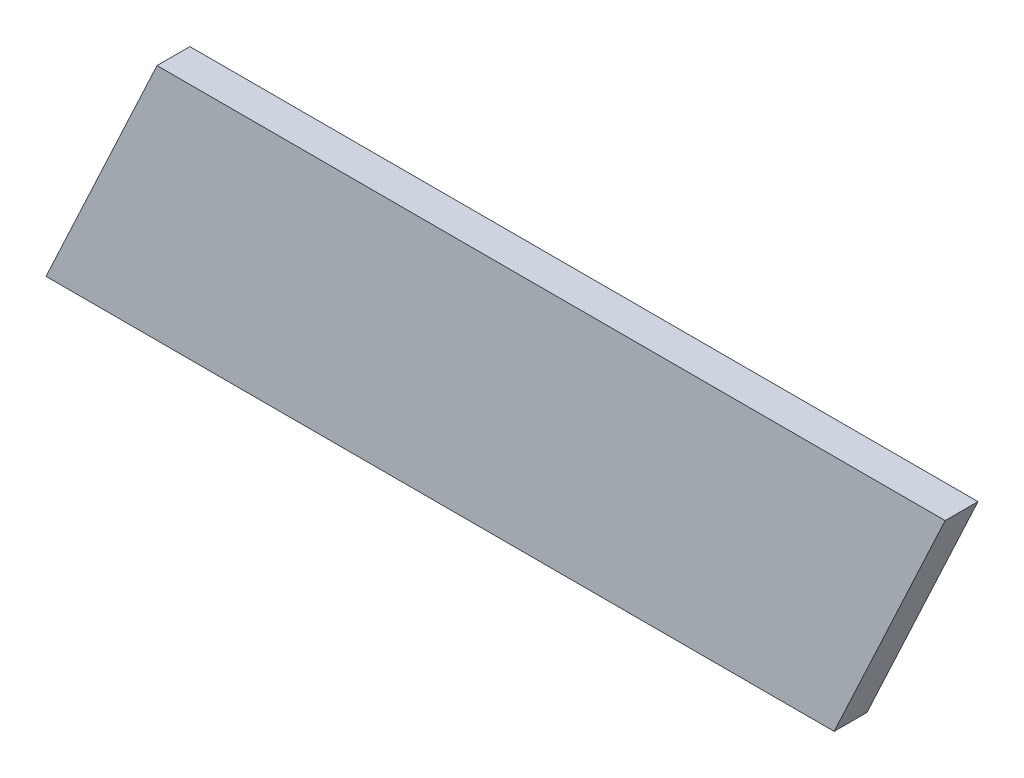
SolidWorks part; units mm, degrees
ref_plane "Front Plane" through (0, 0, 0) normal (0, 0, 1) x (1, 0, 0)
ref_plane "Top Plane" through (0, 0, 0) normal (0, 1, 0) x (1, 0, 0)
ref_plane "Right Plane" through (0, 0, 0) normal (1, 0, 0) x (0, 0, -1)
sketch "Sketch1" plane through (0, 0, 0) normal (0, 0, 1) x (1, 0, 0)
  line L0 (0, 0) -> (120, 0)
  line L1 (0, 0) -> (16.9047, 36.2523)
  line L2 (120, 0) -> (136.9047, 36.2523)
  line L3 (16.9047, 36.2523) -> (136.9047, 36.2523)
  dimension "D1" = 120
  dimension "D2" = 40
  dimension "D3" = 115
extrude "Boss-Extrude1" add sketch "Sketch1" along normal blind 5
